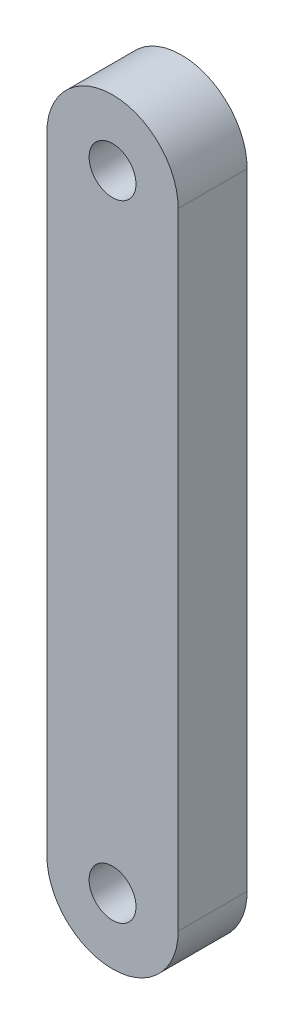
SolidWorks part; units mm, degrees
ref_plane "Front Plane" through (0, 0, 0) normal (0, 0, 1) x (1, 0, 0)
ref_plane "Top Plane" through (0, 0, 0) normal (0, 1, 0) x (1, 0, 0)
ref_plane "Right Plane" through (0, 0, 0) normal (1, 0, 0) x (0, 0, -1)
sketch "Sketch1" plane through (0, 0, 0) normal (0, 0, 1) x (1, 0, 0)
  line L0 (0, 14.4839) -> (0, 59.8657) construction
  line L1 (-4.7623, 14.4839) -> (-4.7623, 59.8657)
  line L2 (4.7623, 14.4839) -> (4.7623, 59.8657)
  arc A0 (-4.7623, 14.4839) -> (4.7623, 14.4839) centre (0, 14.4839) ccw
  arc A1 (4.7623, 59.8657) -> (-4.7623, 59.8657) centre (0, 59.8657) ccw
  circle A2 centre (0, 59.8657) radius 1.7
  circle A3 centre (0, 14.4839) radius 1.7
  point P3 (0, 37.1748)
extrude "Boss-Extrude1" add sketch "Sketch1" along normal blind 5
